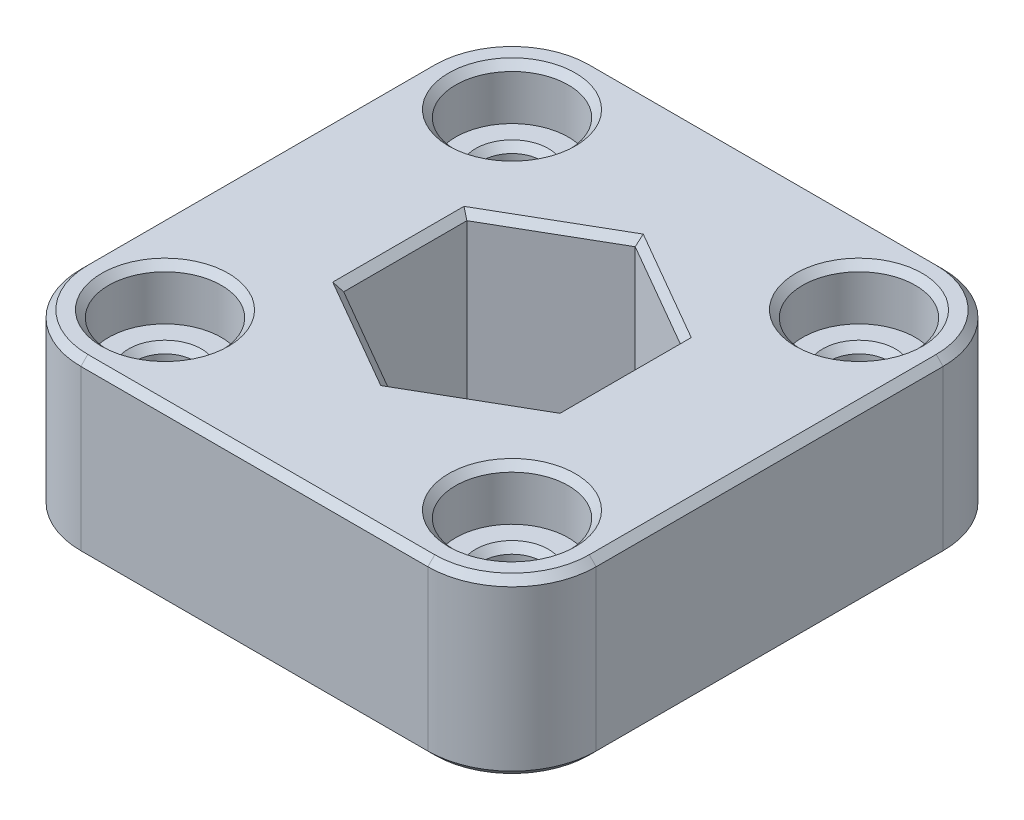
SolidWorks part; units mm, degrees
ref_plane "Front Plane" through (0, 0, 0) normal (0, 0, 1) x (1, 0, 0)
ref_plane "Top Plane" through (0, 0, 0) normal (0, 1, 0) x (1, 0, 0)
ref_plane "Right Plane" through (0, 0, 0) normal (1, 0, 0) x (0, 0, -1)
sketch "Sketch3" plane through (0, 0, 0) normal (0, 1, 0) x (1, 0, 0)
  line L0 (-14.85, -10) -> (-14.85, 10)
  line L1 (-6.15, 3.5507) -> (-6.15, -3.5507)
  line L2 (-6.15, -3.5507) -> (0, -7.1014)
  line L3 (0, -7.1014) -> (6.15, -3.5507)
  line L4 (6.15, -3.5507) -> (6.15, 3.5507)
  line L5 (6.15, 3.5507) -> (0, 7.1014)
  line L6 (0, 7.1014) -> (-6.15, 3.5507)
  line L7 (-10, 14.85) -> (10, 14.85)
  line L8 (14.85, 10) -> (14.85, -10)
  line L9 (10, -14.85) -> (-10, -14.85)
  circle A0 centre (0, 0) radius 6.15 construction
  arc A1 (-10, -14.85) -> (-14.85, -10) centre (-10, -10) cw
  arc A2 (14.85, -10) -> (10, -14.85) centre (10, -10) cw
  arc A3 (10, 14.85) -> (14.85, 10) centre (10, 10) cw
  arc A4 (-14.85, 10) -> (-10, 14.85) centre (-10, 10) cw
  circle A5 centre (-10, -10) radius 3.25 construction
  point P12 (-14.85, 0)
  point P22 (0, 14.85)
  dimension "D2" = 1.6
  dimension "D4" = 6.5
  dimension "D1" = 12.3
  dimension "D3" = 20
extrude "Boss-Extrude1" add sketch "Sketch3" along normal blind 10
hole_wizard "CBORE for M3 SHCS1" positions "Sketch4" profile "Sketch5" counterbore size "M3" standard "ANSI Metric" end condition through all
sketch "Sketch4" plane through (0, 10, 0) normal (0, 1, 0) x (1, 0, 0)
  point P0 (-10, 10)
  point P3 (10, 10)
  point P6 (10, -10)
  point P9 (-10, -10)
sketch "Sketch5" plane through (-10, 10, -10) normal (1, 0, 0) x (0, 0, 1)
  line L0 (0, 0) -> (0, 10)
  line L1 (1.7, 9.6) -> (2.1, 10)
  line L2 (1.7, 9.6) -> (1.7, 3.4)
  line L3 (1.7, 3.4) -> (2.1, 3)
  line L4 (2.1, 3) -> (3.25, 3)
  line L5 (3.25, 3) -> (3.25, 0.4)
  line L6 (3.25, 0.4) -> (3.65, 0)
  line L7 (3.65, 0) -> (0, 0)
  line L8 (-3.25, 0.4) -> (-3.65, 0) construction
  line L9 (-1.7, 3.4) -> (-2.1, 3) construction
  line L11 (0, -6.35) -> (0, 107.95) construction
  line L12 (2.1, 10) -> (0, 10)
  line L13 (-1.7, 9.6) -> (-2.1, 10) construction
  dimension "Thru Hole Dia." = 3.4
  dimension "Thru Hole Depth" = 10
  dimension "C'Bore Dia." = 6.5
  dimension "C'Bore Depth" = 3
  dimension "Near C'Sink Dia." = 7.3
  dimension "Near C'Sink Angle" = 90
  dimension "Mid C'Sink Dia." = 4.2
  dimension "Mid C'Sink Angle" = 90
  dimension "Far C'Sink Dia." = 4.2
  dimension "Far C'Sink Angle" = 90
chamfer "Chamfer1" distance 0.4 angle 45 28 edges at (-3.075, 0, 5.3261) (3.075, 0, 5.3261) (6.15, 0, 0) (3.075, 0, -5.3261) (-3.075, 0, -5.3261) (-6.15, 0, 0) (-14.85, 0, 0) (-13.4295, 0, 13.4295) (-13.4295, 0, -13.4295) (0, 0, 14.85) (0, 0, -14.85) (13.4295, 0, 13.4295) (13.4295, 0, -13.4295) (14.85, 0, 0) (-14.85, 10, 0) (-13.4295, 10, 13.4295) (-13.4295, 10, -13.4295) (0, 10, 14.85) (0, 10, -14.85) (13.4295, 10, 13.4295) (13.4295, 10, -13.4295) (14.85, 10, 0) (3.075, 10, 5.3261) (-3.075, 10, 5.3261) (-6.15, 10, 0) (6.15, 10, 0) (3.075, 10, -5.3261) (-3.075, 10, -5.3261)
